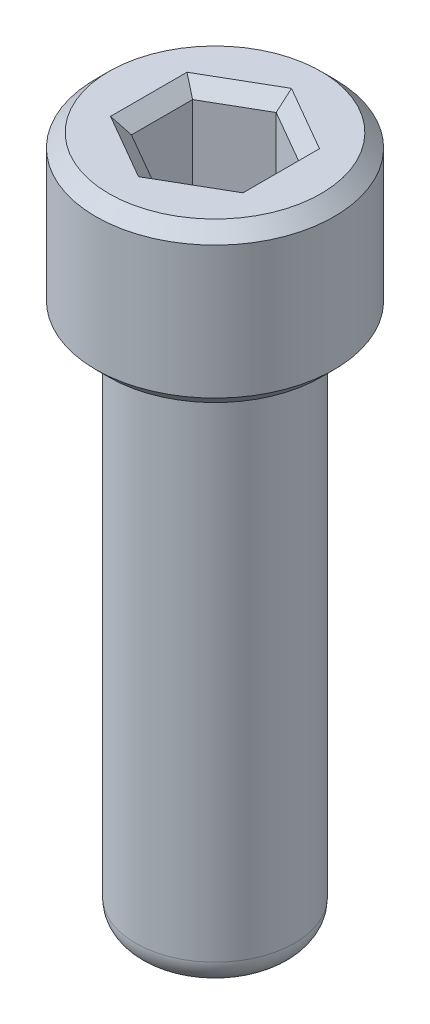
SolidWorks part; units mm, degrees
ref_plane "Front Plane" through (0, 0, 0) normal (0, 0, 1) x (1, 0, 0)
ref_plane "Top Plane" through (0, 0, 0) normal (0, 1, 0) x (1, 0, 0)
ref_plane "Right Plane" through (0, 0, 0) normal (1, 0, 0) x (0, 0, -1)
sketch "Sketch1" plane through (0, 0, 0) normal (0, 1, 0) x (1, 0, 0)
  circle A0 centre (0, 0) radius 1.5
  dimension "D1" = 3
extrude "Boss-Extrude1" add sketch "Sketch1" along normal blind 10
sketch "Sketch2" plane through (0, 10, 0) normal (0, 1, 0) x (1, 0, 0)
  circle A0 centre (0, 0) radius 2.25
  dimension "D1" = 4.5
extrude "Boss-Extrude2" add sketch "Sketch2" along normal blind 3
sketch "Sketch3" plane through (0, 13, 0) normal (0, 1, 0) x (1, 0, 0)
  line L1 (0, 1.1547) -> (-1, 0.5774)
  line L2 (-1, 0.5774) -> (-1, -0.5774)
  line L3 (-1, -0.5774) -> (0, -1.1547)
  line L4 (0, -1.1547) -> (1, -0.5774)
  line L5 (1, -0.5774) -> (1, 0.5774)
  line L6 (1, 0.5774) -> (0, 1.1547)
  circle A0 centre (0, 0) radius 1 construction
extrude "Cut-Extrude1" cut sketch "Sketch3" against normal blind 2
chamfer "Chamfer1" distance 0.25 angle 45 8 edges at (0, 10, 2.25) (0, 13, 2.25) (-0.5, 13, 0.866) (-1, 13, 0) (-0.5, 13, -0.866) (0.5, 13, -0.866) (1, 13, 0) (0.5, 13, 0.866)
fillet "Fillet1" radius 0.5 1 edges at (0, 0, 1.5)
